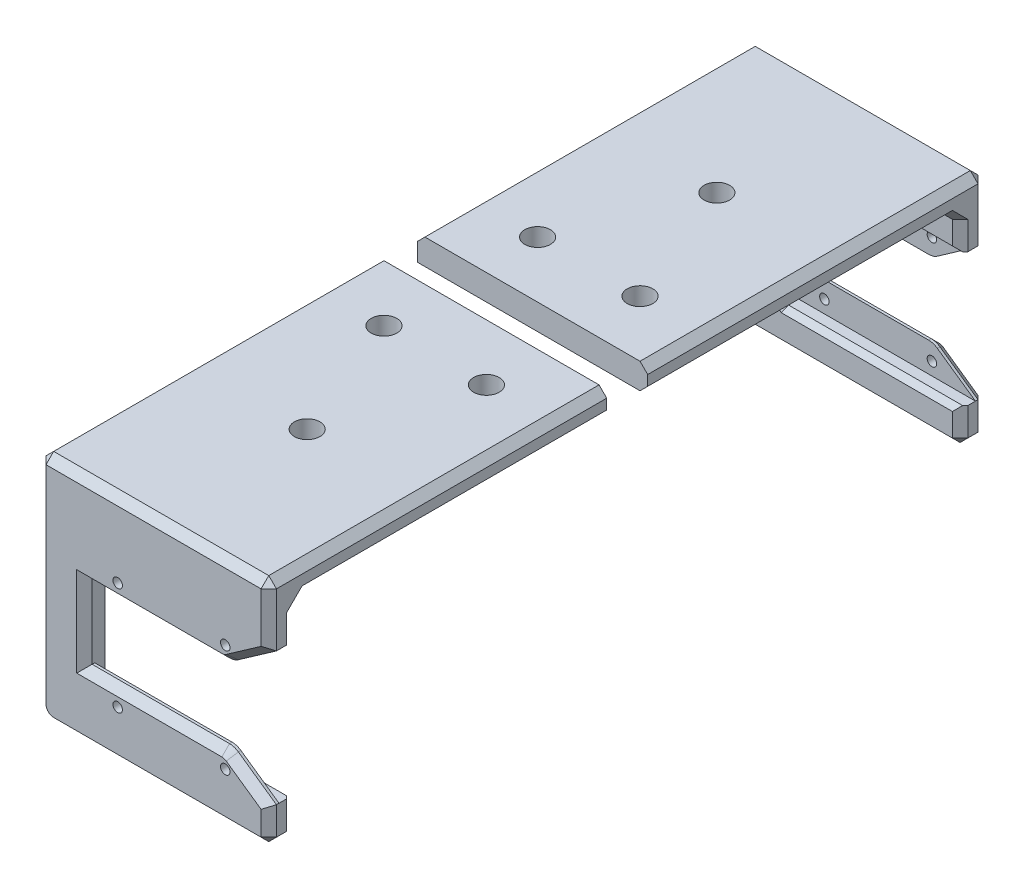
SolidWorks part; units mm, degrees
ref_plane "前视基准面" through (0, 0, 0) normal (0, 0, 1) x (1, 0, 0)
ref_plane "上视基准面" through (0, 0, 0) normal (0, 1, 0) x (1, 0, 0)
ref_plane "右视基准面" through (0, 0, 0) normal (1, 0, 0) x (0, 0, -1)
other "Configuration Table"
sketch "草图1" plane through (0, 0, 0) normal (0, 0, 1) x (1, 0, 0)
  line L1 (-42, -20) -> (0, -20)
  line L2 (-45, -17) -> (-45, 20)
  line L3 (-45, 20) -> (0, 20)
  arc A0 (0, 20) -> (0, -20) centre (0, 0) cw
  arc A1 (-42, -20) -> (-45, -17) centre (-42, -17) cw
  point P0 (0, 0)
  point P2 (0, 0)
  point P12 (0, 0)
  point P14 (0, 0)
  dimension "D1" = 3
  dimension "D3" = 20
  dimension "D2" = 45
extrude "凸台-拉伸1" add sketch "草图1" along normal blind 5
sketch "草图2" plane through (0, 0, 0) normal (0, 0, -1) x (-1, 0, 0)
  line L0 (0, 0) -> (62.6609, 0) construction
  line L2 (0, -13) -> (36, -13)
  line L3 (0, -13) -> (0, 13)
  line L4 (0, 13) -> (36, 13)
  line L5 (36, -13) -> (36, 13)
  line L6 (0, -13) -> (36, 13) construction
  line L7 (0, 13) -> (36, -13) construction
  point P3 (18, 0)
  point P9 (0, 0)
  point P10 (-0.0617, -15.1873)
  point P11 (0, 0)
  dimension "D1" = 26
  dimension "D2" = 36
extrude "切除-拉伸1" cut sketch "草图2" against normal blind 3
sketch "草图3" plane through (0, 0, 0) normal (0, 0, -1) x (-1, 0, 0)
  line L2 (0, -20) -> (0, 20)
  arc A1 (0, 20) -> (0, -20) centre (0, 0) ccw
extrude "切除-拉伸2" cut sketch "草图3" against normal through all
sketch "草图4" plane through (0, 0, 3) normal (0, 0, -1) x (-1, 0, 0)
  line L0 (0, 0) -> (56.6481, 0) construction
  line L1 (8.5, 10.5) -> (29.5, 10.5) construction
  line L2 (8.5, -10.5) -> (29.5, -10.5) construction
  line L3 (36, -13) -> (36, 13) construction
  line L4 (8.2119, -7.25) -> (36, -7.25)
  line L6 (8.2119, 7.25) -> (36, 7.25)
  line L7 (36, -7.25) -> (36, 7.25)
  line L8 (-5.9833, -9.7474) -> (36, 7.25) construction
  line L9 (-5.9833, 9.7474) -> (36, -7.25) construction
  line L10 (0, 13) -> (8.2119, 7.25)
  line L11 (0, -13) -> (8.2119, -7.25)
  line L12 (0, -13) -> (0, 13)
  line L13 (36, 13) -> (0, 13) construction
  circle A0 centre (8.5, 10.5) radius 0.925
  circle A1 centre (8.5, -10.5) radius 0.925
  circle A2 centre (29.5, 10.5) radius 0.925
  circle A3 centre (29.5, -10.5) radius 0.925
  point P14 (18.0926, 0)
  point P24 (0, -15)
  point P25 (0, 15)
  point P29 (7.787, -7.25)
  point P30 (6.9688, 7.25)
  dimension "D1" = 1.85
  dimension "D2" = 1.85
  dimension "D3" = 21
  dimension "D4" = 21
  dimension "D5" = 8.5
  dimension "D6" = 14.5
  dimension "D7" = 35
  dimension "D8" = 35
extrude "切除-拉伸3" cut sketch "草图4" against normal through all
chamfer "倒角1" distance 1.5 angle 45 2 edges at (-36, 13, 1.5) (-36, -13, 1.5)
chamfer "倒角2" distance 1 angle 45 5 edges at (-17.25, -13, 0) (-35.25, -12.25, 0) (-36, 0, 0) (-35.25, 12.25, 0) (-17.25, 13, 0)
fillet "圆角3" radius 3 2 edges at (-8.2119, -7.25, 4) (-8.2119, 7.25, 4)
sketch "草图7" plane through (0, 20, 0) normal (0, 1, 0) x (1, 0, 0)
  line L1 (-45, -5) -> (0, -5)
  line L2 (-45, -5) -> (-45, 135)
  line L3 (-45, 135) -> (0, 135)
  line L4 (0, -5) -> (0, 135)
  line L6 (-45, -5) -> (-45, 0) construction
  point P5 (5, 0)
  point P6 (5, 0)
  point P7 (0, 0)
  point P8 (-45, -5)
  dimension "D1" = 140
extrude "凸台-拉伸2" add sketch "草图7" along normal blind 5 contours L2 L3 L4 L1
sketch "草图9" plane through (0, 25, 0) normal (0, 1, 0) x (1, 0, 0)
  line L0 (-45, -5) -> (-45, 135) construction
  line L1 (-32.5, 50) -> (-12.5, 50) construction
  line L2 (-32.5, 50) -> (-32.5, 80) construction
  line L3 (-32.5, 80) -> (-12.5, 80) construction
  line L4 (-12.5, 50) -> (-12.5, 80) construction
  line L7 (-45, 65) -> (16.0436, 65) construction
  line L8 (-22.5, -5) -> (-22.5, 135) construction
  line L9 (-45, -5) -> (0, -5) construction
  line L10 (-45, 135) -> (0, 135) construction
  circle A0 centre (-12.5, 80) radius 2.5
  circle A1 centre (-32.5, 80) radius 2.5
  circle A2 centre (-32.5, 50) radius 2.5
  circle A3 centre (-12.5, 50) radius 2.5
  circle A4 centre (-22.5, 25) radius 2.5
  circle A5 centre (-22.5, 105) radius 2.5
  dimension "D5" = 5
  dimension "D1" = 30
  dimension "D2" = 20
  dimension "D3" = 12.5
  dimension "D4" = 25
extrude "切除-拉伸5" cut sketch "草图9" against normal through all
sketch "草图10" plane through (0, 25, 0) normal (0, 1, 0) x (1, 0, 0)
  line L0 (-45, 65) -> (0, 65) construction
  line L1 (-45, -5) -> (-45, 135) construction
  line L2 (0, -5) -> (0, 135) construction
ref_plane "基准面1" through (0, 0, -65) normal (0, 0, 1) x (1, 0, 0)
mirror "镜向1" about plane through (0, 0, -65) normal (0, 0, 1) of "圆角3", "凸台-拉伸1", "切除-拉伸1", "切除-拉伸2", "切除-拉伸3", "倒角1", "倒角2"
sketch "草图11" plane through (-45, 0, 0) normal (-1, 0, 0) x (0, 0, 1)
  line L0 (-130, 1.5) -> (-111.5, 20)
  line L1 (0, 20) -> (-130, 20) construction
  line L2 (0, 0) -> (-20, 20)
  line L3 (-65, -50.177) -> (-65, 50.177) construction
  line L4 (-65, 25) -> (-65, -20.8815) construction
  line L5 (5, 25) -> (-135, 25) construction
  line L6 (-130, 1.5) -> (-130, 20)
  line L7 (-130, 20) -> (-111.5, 20)
  line L9 (0, 20) -> (-20, 20)
  line L10 (0, 20) -> (0, -17) construction
  line L11 (-130, 20) -> (-130, -17) construction
  point P7 (-42.5178, 25)
  point P14 (0, -17)
  point P18 (-40.2934, 20)
  point P19 (0, 20)
  point P21 (2.7827, 20)
  point P22 (-43.4591, 25)
  point P23 (0, 0)
  point P24 (0, 20)
  point P26 (0, -17)
  point P27 (0, 0)
  point P29 (-22.6571, 20)
  point P30 (-130, 0)
  point P31 (-108.4551, 20)
  point P34 (-130, 1.5)
  dimension "D1" = 45
  dimension "D2" = 45
extrude "凸台-拉伸3" add sketch "草图11" against normal blind 3
chamfer "倒角4" distance 1.5 angle 45 46 edges at (-3.7185, -10.3963, 5) (-8.2556, -7.3888, 5) (-22.5789, -7.25, 5) (-36, 0, 5) (-3.7185, -10.3963, -135) (-8.2556, -7.3888, -135) (-22.5789, -7.25, -135) (-36, 0, -135) (-42, 20, -120.75) (-42, 10.75, -130) (-22.5789, 7.25, 5) (-22.5789, 7.25, -135) (-21, -20, -135) (-8.2556, 7.3888, 5) (-8.2556, 7.3888, -135) (-44.1213, -19.1213, -135) (-3.7185, 10.3963, 5) (0, 19, 5) (-3.7185, 10.3963, -135) (0, 19, -135) (0, 25, -65) (-22.5, 25, -135) (-45, 4, -135) (-45, 25, -65) (-22.5, 25, 5) (0, -17, 0) (0, 17, -130) (0, 20, -65) (-42, 20, -10) (-42, 10, 0) (-21, 20, 0) (-45, -7.75, -130) (-44.1213, -19.1213, -130) (0, -17, -130) (0, -16.5, -135) (-21, -20, -130) (0, -20, -132.5) (-45, -8.5, 0) (-45, 4, 5) (-44.1213, -19.1213, 0) (-44.1213, -19.1213, 5) (0, -16.5, 5) (-21, -20, 0) (-21, -20, 5) (0, -20, 2.5) (-21, 20, -130)
sketch "草图12" plane through (0, 25, 0) normal (0, 1, 0) x (1, 0, 0)
  line L0 (-45, 65) -> (0, 65) construction
  line L1 (0, -5) -> (0, 135) construction
  line L2 (-45, 61) -> (0, 61)
  line L3 (-45, 61) -> (-45, 69)
  line L4 (-45, 69) -> (0, 69)
  line L5 (0, 61) -> (0, 69)
  line L6 (-45, 61) -> (0, 69) construction
  line L7 (-45, 69) -> (0, 61) construction
  point P4 (-22.5, 65)
  dimension "D1" = 8
extrude "切除-拉伸6" cut sketch "草图12" against normal through all
